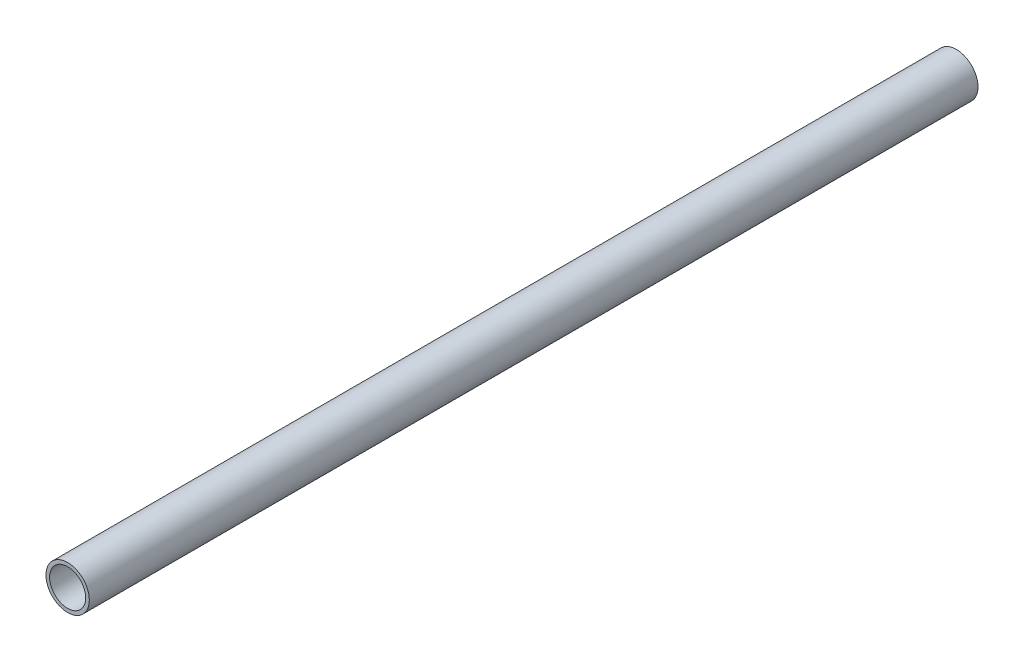
SolidWorks part; units mm, degrees
ref_plane "Front Plane" through (0, 0, 0) normal (0, 0, 1) x (1, 0, 0)
ref_plane "Top Plane" through (0, 0, 0) normal (0, 1, 0) x (1, 0, 0)
ref_plane "Right Plane" through (0, 0, 0) normal (1, 0, 0) x (0, 0, -1)
sketch "Sketch1" plane through (0, 0, 0) normal (0, 0, 1) x (1, 0, 0)
  circle A0 centre (0, 0) radius 5
  circle A1 centre (0, 0) radius 6
  dimension "D2" = 12
  dimension "D1" = 1
extrude "Boss-Extrude1" add sketch "Sketch1" along normal blind 246
